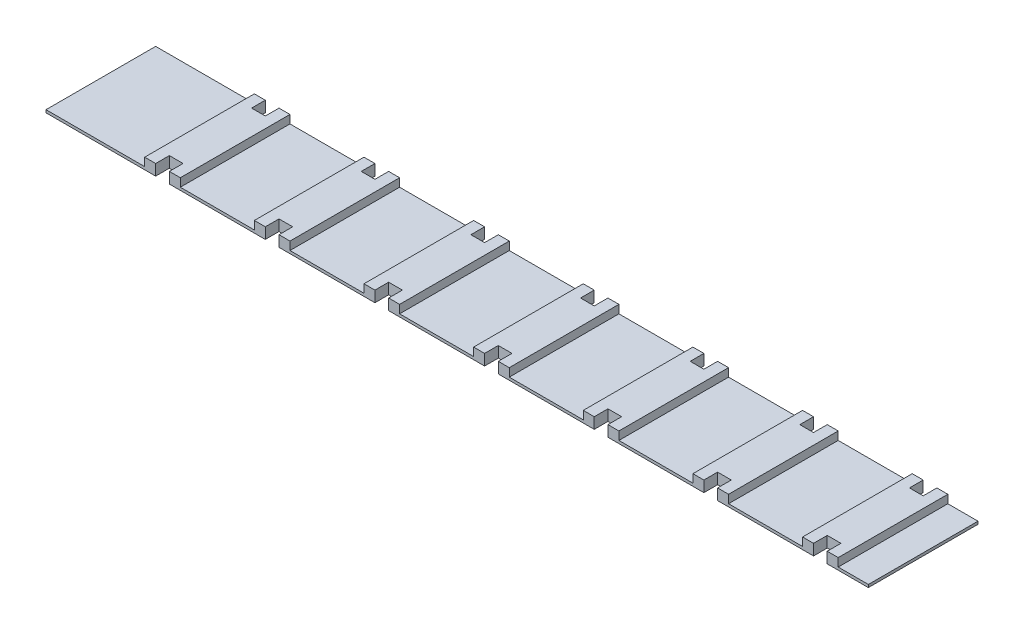
SolidWorks part; units mm, degrees
ref_plane "Front Plane" through (0, 0, 0) normal (0, 0, 1) x (1, 0, 0)
ref_plane "Top Plane" through (0, 0, 0) normal (0, 1, 0) x (1, 0, 0)
ref_plane "Right Plane" through (0, 0, 0) normal (1, 0, 0) x (0, 0, -1)
sketch "Sketch1" plane through (0, 0, 0) normal (0, 1, 0) x (1, 0, 0)
  line L0 (40, 0) -> (40, 2.5)
  line L1 (0, 0) -> (20, 0)
  line L2 (0, 0) -> (0, 20)
  line L3 (0, 20) -> (20, 20)
  line L4 (150, 0) -> (150, 20)
  line L6 (20, 20) -> (20, 17.5)
  line L7 (20, 17.5) -> (22.5, 17.5)
  line L8 (22.5, 20) -> (22.5, 17.5)
  line L10 (20, 0) -> (20, 2.5)
  line L11 (20, 2.5) -> (22.5, 2.5)
  line L12 (22.5, 0) -> (22.5, 2.5)
  line L14 (42.5, 0) -> (42.5, 2.5)
  line L15 (40, 2.5) -> (42.5, 2.5)
  line L16 (40, 20) -> (40, 17.5)
  line L18 (42.5, 20) -> (42.5, 17.5)
  line L19 (40, 17.5) -> (42.5, 17.5)
  line L20 (60, 0) -> (60, 2.5)
  line L22 (62.5, 0) -> (62.5, 2.5)
  line L23 (60, 2.5) -> (62.5, 2.5)
  line L24 (60, 20) -> (60, 17.5)
  line L26 (62.5, 20) -> (62.5, 17.5)
  line L27 (60, 17.5) -> (62.5, 17.5)
  line L28 (80, 0) -> (80, 2.5)
  line L30 (82.5, 0) -> (82.5, 2.5)
  line L31 (80, 2.5) -> (82.5, 2.5)
  line L32 (80, 20) -> (80, 17.5)
  line L34 (82.5, 20) -> (82.5, 17.5)
  line L35 (80, 17.5) -> (82.5, 17.5)
  line L36 (100, 0) -> (100, 2.5)
  line L38 (102.5, 0) -> (102.5, 2.5)
  line L39 (100, 2.5) -> (102.5, 2.5)
  line L40 (100, 20) -> (100, 17.5)
  line L42 (102.5, 20) -> (102.5, 17.5)
  line L43 (100, 17.5) -> (102.5, 17.5)
  line L44 (120, 0) -> (120, 2.5)
  line L46 (122.5, 0) -> (122.5, 2.5)
  line L47 (120, 2.5) -> (122.5, 2.5)
  line L48 (120, 20) -> (120, 17.5)
  line L50 (122.5, 20) -> (122.5, 17.5)
  line L51 (120, 17.5) -> (122.5, 17.5)
  line L52 (140, 0) -> (140, 2.5)
  line L54 (142.5, 0) -> (142.5, 2.5)
  line L55 (140, 2.5) -> (142.5, 2.5)
  line L56 (140, 20) -> (140, 17.5)
  line L58 (142.5, 20) -> (142.5, 17.5)
  line L59 (140, 17.5) -> (142.5, 17.5)
  line L60 (22.5, 0) -> (40, 0)
  line L61 (22.5, 20) -> (40, 20)
  line L62 (42.5, 20) -> (60, 20)
  line L63 (62.5, 20) -> (80, 20)
  line L64 (82.5, 20) -> (100, 20)
  line L65 (102.5, 20) -> (120, 20)
  line L66 (122.5, 20) -> (140, 20)
  line L67 (142.5, 20) -> (150, 20)
  line L68 (142.5, 0) -> (150, 0)
  line L69 (122.5, 0) -> (140, 0)
  line L70 (102.5, 0) -> (120, 0)
  line L71 (82.5, 0) -> (100, 0)
  line L72 (62.5, 0) -> (80, 0)
  line L73 (42.5, 0) -> (60, 0)
  dimension "D1" = 150
  dimension "D2" = 20
  dimension "D3" = 22.5
  dimension "D4" = 40
  dimension "D5" = 2.5
  dimension "D6" = 17.5
  dimension "D8" = 7
extrude "Boss-Extrude1" add sketch "Sketch1" along normal blind 0.5
sketch "Sketch2" plane through (0, 0.5, 0) normal (0, 1, 0) x (1, 0, 0)
  line L0 (20, 20) -> (18, 20)
  line L1 (20, 20) -> (0, 20) construction
  line L2 (18, 20) -> (18, 0)
  line L3 (0, 0) -> (20, 0) construction
  line L4 (18, 0) -> (20, 0)
  line L5 (20, 0) -> (20, 2.5)
  line L6 (20, 2.5) -> (22.5, 2.5)
  line L7 (22.5, 2.5) -> (22.5, 0)
  line L8 (22.5, 0) -> (24.5, 0)
  line L9 (22.5, 0) -> (40, 0) construction
  line L10 (24.5, 0) -> (24.5, 20)
  line L11 (40, 20) -> (22.5, 20) construction
  line L12 (24.5, 20) -> (22.5, 20)
  line L13 (22.5, 20) -> (22.5, 17.5)
  line L14 (22.5, 17.5) -> (20, 17.5)
  line L15 (20, 17.5) -> (20, 20) construction
  line L16 (22.5, 17.5) -> (20, 17.5) construction
  line L17 (20, 17.5) -> (20, 20)
  line L18 (40, 17.5) -> (40, 20)
  line L19 (40, 20) -> (38, 20)
  line L20 (38, 20) -> (38, 0)
  line L21 (38, 0) -> (40, 0)
  line L22 (40, 0) -> (40, 2.5)
  line L23 (40, 2.5) -> (42.5, 2.5)
  line L24 (42.5, 2.5) -> (42.5, 0)
  line L25 (42.5, 0) -> (44.5, 0)
  line L26 (44.5, 0) -> (44.5, 20)
  line L27 (44.5, 20) -> (42.5, 20)
  line L28 (42.5, 20) -> (42.5, 17.5)
  line L29 (42.5, 17.5) -> (40, 17.5)
  line L30 (60, 17.5) -> (60, 20)
  line L31 (60, 20) -> (58, 20)
  line L32 (58, 20) -> (58, 0)
  line L33 (58, 0) -> (60, 0)
  line L34 (60, 0) -> (60, 2.5)
  line L35 (60, 2.5) -> (62.5, 2.5)
  line L36 (62.5, 2.5) -> (62.5, 0)
  line L37 (62.5, 0) -> (64.5, 0)
  line L38 (64.5, 0) -> (64.5, 20)
  line L39 (64.5, 20) -> (62.5, 20)
  line L40 (62.5, 20) -> (62.5, 17.5)
  line L41 (62.5, 17.5) -> (60, 17.5)
  line L42 (80, 17.5) -> (80, 20)
  line L43 (80, 20) -> (78, 20)
  line L44 (78, 20) -> (78, 0)
  line L45 (78, 0) -> (80, 0)
  line L46 (80, 0) -> (80, 2.5)
  line L47 (80, 2.5) -> (82.5, 2.5)
  line L48 (82.5, 2.5) -> (82.5, 0)
  line L49 (82.5, 0) -> (84.5, 0)
  line L50 (84.5, 0) -> (84.5, 20)
  line L51 (84.5, 20) -> (82.5, 20)
  line L52 (82.5, 20) -> (82.5, 17.5)
  line L53 (82.5, 17.5) -> (80, 17.5)
  line L54 (100, 17.5) -> (100, 20)
  line L55 (100, 20) -> (98, 20)
  line L56 (98, 20) -> (98, 0)
  line L57 (98, 0) -> (100, 0)
  line L58 (100, 0) -> (100, 2.5)
  line L59 (100, 2.5) -> (102.5, 2.5)
  line L60 (102.5, 2.5) -> (102.5, 0)
  line L61 (102.5, 0) -> (104.5, 0)
  line L62 (104.5, 0) -> (104.5, 20)
  line L63 (104.5, 20) -> (102.5, 20)
  line L64 (102.5, 20) -> (102.5, 17.5)
  line L65 (102.5, 17.5) -> (100, 17.5)
  line L66 (120, 17.5) -> (120, 20)
  line L67 (120, 20) -> (118, 20)
  line L68 (118, 20) -> (118, 0)
  line L69 (118, 0) -> (120, 0)
  line L70 (120, 0) -> (120, 2.5)
  line L71 (120, 2.5) -> (122.5, 2.5)
  line L72 (122.5, 2.5) -> (122.5, 0)
  line L73 (122.5, 0) -> (124.5, 0)
  line L74 (124.5, 0) -> (124.5, 20)
  line L75 (124.5, 20) -> (122.5, 20)
  line L76 (122.5, 20) -> (122.5, 17.5)
  line L77 (122.5, 17.5) -> (120, 17.5)
  line L78 (140, 17.5) -> (140, 20)
  line L79 (140, 20) -> (138, 20)
  line L80 (138, 20) -> (138, 0)
  line L81 (138, 0) -> (140, 0)
  line L82 (140, 0) -> (140, 2.5)
  line L83 (140, 2.5) -> (142.5, 2.5)
  line L84 (142.5, 2.5) -> (142.5, 0)
  line L85 (142.5, 0) -> (144.5, 0)
  line L86 (144.5, 0) -> (144.5, 20)
  line L87 (144.5, 20) -> (142.5, 20)
  line L88 (142.5, 20) -> (142.5, 17.5)
  line L89 (142.5, 17.5) -> (140, 17.5)
  line L90 (0, 20) -> (0, 0) construction
  dimension "D1" = 2
  dimension "D2" = 2
  dimension "D4" = 38
  dimension "D3" = 7
extrude "Boss-Extrude2" add sketch "Sketch2" along normal blind 1.5
